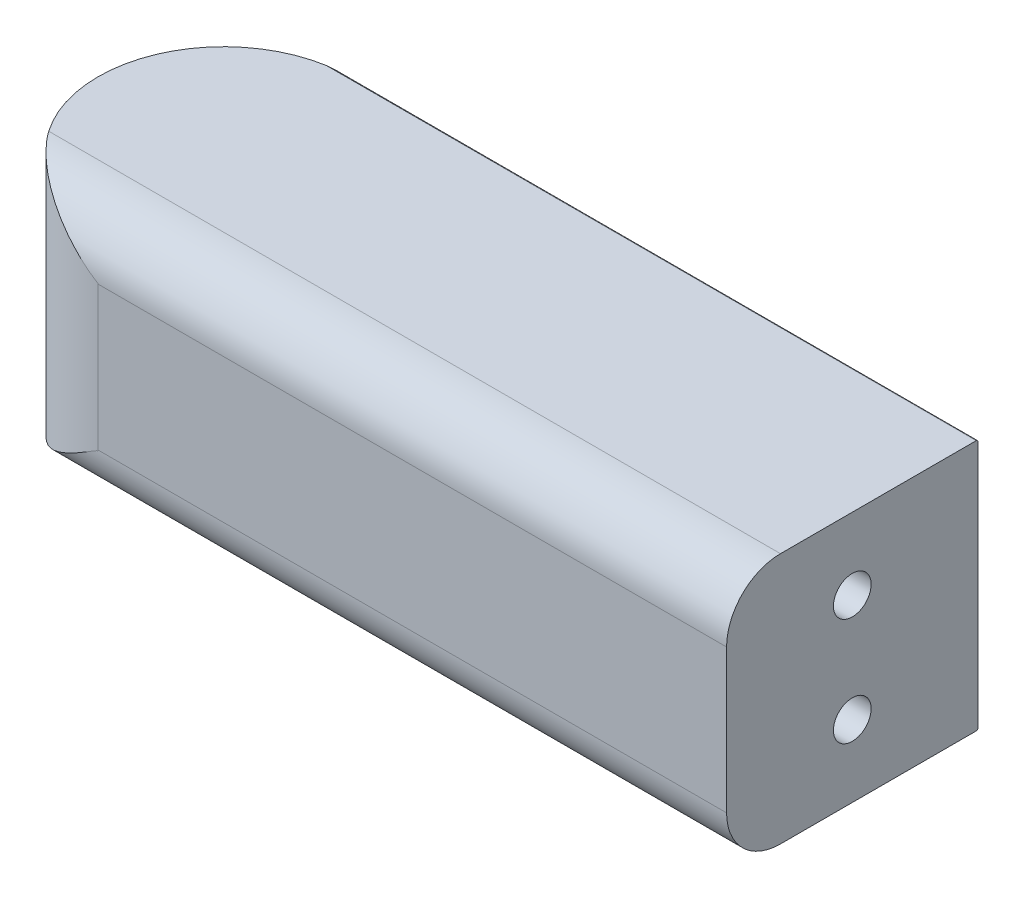
SolidWorks part; units mm, degrees
ref_plane "Front Plane" through (0, 0, 0) normal (0, 0, 1) x (1, 0, 0)
ref_plane "Top Plane" through (0, 0, 0) normal (0, 1, 0) x (1, 0, 0)
ref_plane "Right Plane" through (0, 0, 0) normal (1, 0, 0) x (0, 0, -1)
sketch "Sketch1" plane through (0, 0, 0) normal (0, 1, 0) x (1, 0, 0)
  line L1 (0, 0) -> (350, 0)
  line L2 (0, 0) -> (0, -140)
  line L3 (0, -140) -> (350, -140)
  line L4 (350, 0) -> (350, -140)
  circle A0 centre (0, -70) radius 69.995
  dimension "D3" = 139.99
  dimension "D1" = 140
  dimension "D2" = 350
extrude "Boss-Extrude1" add sketch "Sketch1" along normal blind 140 contours A0 L3 L4 L1 | L2 A0 | L2 A0
ref_plane "Plane1" through (-70, 0, 0) normal (1, 0, 0) x (0, 0, -1)
sketch "Sketch2" plane through (-70, 0, 0) normal (1, 0, 0) x (0, 0, -1)
  line L1 (-139.995, 0) -> (-0.005, 0) construction
  line L2 (-0.005, 140) -> (-139.995, 140) construction
  line L3 (0, 140) -> (0, 0) construction
  circle A0 centre (-70, 100) radius 10.5
  circle A1 centre (-70, 40) radius 10.5
  dimension "D5" = 21
  dimension "D6" = 21
  dimension "D1" = 70
  dimension "D2" = 70
  dimension "D3" = 40
  dimension "D4" = 40
extrude "Cut-Extrude3" cut sketch "Sketch2" along normal blind 41
fillet "Fillet2" radius 30 2 edges at (175, 140, 140) (175, 0, 140)
fillet "Fillet3" radius 1 2 edges at (175, 140, 0) (175, 0, 0)
sketch "Sketch3" plane through (350, 0, 0) normal (1, 0, 0) x (0, 0, -1)
  line L0 (0, 139) -> (0, 1) construction
  line L1 (-1, 140) -> (-110, 140) construction
  line L2 (-1, 0) -> (-110, 0) construction
  circle A0 centre (-70, 100) radius 10.5
  circle A1 centre (-70, 40) radius 10.5
  dimension "D3" = 21
  dimension "D4" = 21
  dimension "D6" = 40
  dimension "D1" = 70
  dimension "D2" = 70
  dimension "D5" = 40
extrude "Cut-Extrude4" cut sketch "Sketch3" against normal blind 41
